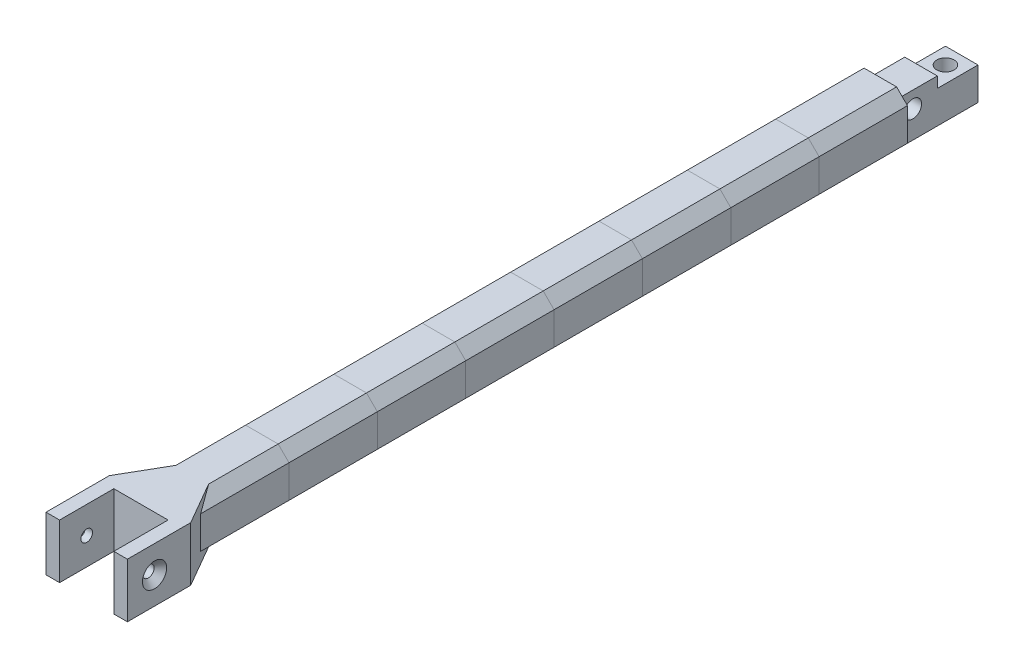
SolidWorks part; units mm, degrees
ref_plane "Front Plane" through (0, 0, 0) normal (0, 0, 1) x (1, 0, 0)
ref_plane "Top Plane" through (0, 0, 0) normal (0, 1, 0) x (1, 0, 0)
ref_plane "Right Plane" through (0, 0, 0) normal (1, 0, 0) x (0, 0, -1)
sketch "Sketch1" plane through (0, 0, 0) normal (0, 0, 1) x (1, 0, 0)
  line L1 (-10, -10) -> (10, -10)
  line L2 (-10, -10) -> (-10, 10)
  line L3 (-10, 10) -> (10, 10)
  line L4 (10, -10) -> (10, 10)
  line L5 (-10, -10) -> (10, 10) construction
  line L6 (-10, 10) -> (10, -10) construction
  point P0 (0, 0)
  dimension "D1" = 20
extrude "Boss-Extrude1" add sketch "Sketch1" along normal blind 302.5
sketch "Sketch2" plane through (0, 10, 0) normal (0, 1, 0) x (1, 0, 0)
  line L0 (0, -302.5) -> (0, -322.5) construction
  line L1 (10, -302.5) -> (-10, -302.5) construction
  line L2 (10, -302.5) -> (10, -322.5)
  line L3 (10, -322.5) -> (15, -322.5)
  line L4 (15, -322.5) -> (15, -299.1603)
  line L5 (15, -299.1603) -> (10, -290.5)
  line L6 (10, -302.5) -> (10, 0) construction
  line L7 (10, -290.5) -> (10, -302.5)
  line L8 (-10, -290.5) -> (-10, -302.5)
  line L9 (-15, -299.1603) -> (-10, -290.5)
  line L10 (-15, -322.5) -> (-15, -299.1603)
  line L11 (-10, -322.5) -> (-15, -322.5)
  line L12 (-10, -302.5) -> (-10, -322.5)
  point P10 (0, 0)
  dimension "D1" = 20
  dimension "D2" = 5
  dimension "D3" = 30
  dimension "D4" = 12
extrude "Boss-Extrude2" add sketch "Sketch2" against normal up to surface (20 mm away) up to face at (0, -10, 151.25)
sketch "Sketch3" plane through (15, 0, 0) normal (1, 0, 0) x (0, 0, -1)
  line L0 (-312.5, 10) -> (-312.5, -10) construction
  line L1 (-322.5, 10) -> (-299.1603, 10) construction
  line L2 (-299.1603, -10) -> (-322.5, -10) construction
  line L3 (-322.5, -10) -> (-322.5, 10) construction
  circle A0 centre (-312.5, 0) radius 2.15
  dimension "D2" = 4.3
  dimension "D1" = 10
extrude "Cut-Extrude1" cut sketch "Sketch3" against normal through all
sketch "Sketch4" plane through (0, 10, 0) normal (0, 1, 0) x (1, 0, 0)
  line L1 (-10, 0) -> (-6, 0)
  line L2 (-10, 0) -> (-10, -30)
  line L3 (-10, -30) -> (-6, -30)
  line L4 (-6, 0) -> (-6, -30)
  line L5 (10, 0) -> (6, 0)
  line L6 (10, 0) -> (10, -30)
  line L7 (10, -30) -> (6, -30)
  line L8 (6, 0) -> (6, -30)
  dimension "D1" = 30
  dimension "D2" = 12
extrude "Cut-Extrude2" cut sketch "Sketch4" against normal through all
chamfer "Chamfer1" distance 2.3 angle 45 2 edges at (-15, 0, 310.35) (15, 0, 310.35)
sketch "Sketch5" plane through (6, 0, 0) normal (1, 0, 0) x (0, 0, -1)
  line L1 (0, 10) -> (-15, 10)
  line L2 (0, 10) -> (0, 2)
  line L3 (0, 2) -> (-15, 2)
  line L4 (-15, 10) -> (-15, 2)
  line L5 (0, -10) -> (-30, -10) construction
  dimension "D1" = 12
  dimension "D2" = 15
extrude "Cut-Extrude3" cut sketch "Sketch5" against normal through all
sketch "Sketch6" plane through (0, 2, 0) normal (0, 1, 0) x (1, 0, 0)
  line L0 (-6, 0) -> (6, 0) construction
  circle A0 centre (0, -6) radius 3.2
  dimension "D1" = 6.4
  dimension "D2" = 6
extrude "Cut-Extrude4" cut sketch "Sketch6" against normal through all
sketch "Sketch7" plane through (6, 0, 0) normal (1, 0, 0) x (0, 0, -1)
  line L1 (-30, -10) -> (-30, 10) construction
  line L2 (-15, 10) -> (-30, 10) construction
  circle A0 centre (-24, 0) radius 3.2
  dimension "D1" = 6.4
  dimension "D2" = 6
  dimension "D3" = 10
extrude "Cut-Extrude5" cut sketch "Sketch7" against normal through all
sketch "Sketch10" plane through (0, 10, 0) normal (0, 1, 0) x (1, 0, 0)
  line L0 (10, -290.5) -> (10, -30) construction
  line L1 (-10, -30) -> (10, -30)
  line L2 (-10, -30) -> (-10, -62.5625)
  line L3 (-10, -62.5625) -> (10, -62.5625)
  line L4 (10, -30) -> (10, -62.5625)
  line L5 (-10, -290.5) -> (-10, -30) construction
  line L6 (10, -95.125) -> (-10, -95.125)
  line L7 (10, -95.125) -> (10, -127.6875)
  line L8 (10, -127.6875) -> (-10, -127.6875)
  line L9 (-10, -95.125) -> (-10, -127.6875)
  line L10 (10, -62.5625) -> (10, -95.125) construction
  line L11 (-10, -160.25) -> (10, -160.25)
  line L12 (-10, -160.25) -> (-10, -192.8125)
  line L13 (-10, -192.8125) -> (10, -192.8125)
  line L14 (10, -160.25) -> (10, -192.8125)
  line L15 (10, -225.375) -> (-10, -225.375)
  line L16 (10, -225.375) -> (10, -257.9375)
  line L17 (10, -257.9375) -> (-10, -257.9375)
  line L18 (-10, -225.375) -> (-10, -257.9375)
  line L19 (10, -127.6875) -> (10, -160.25) construction
  line L20 (10, -192.8125) -> (10, -225.375) construction
  line L21 (10, -257.9375) -> (10, -290.5) construction
extrude "Cut-Extrude7" cut sketch "Sketch10" against normal through all
sketch "Sketch11" plane through (0, 10, 0) normal (0, 1, 0) x (1, 0, 0)
  line L0 (-6, -30) -> (6, -30) construction
  line L1 (-10, -62.5625) -> (10, -62.5625)
  line L2 (-10, -62.5625) -> (-10, -30)
  line L3 (-10, -30) -> (10, -30)
  line L4 (10, -62.5625) -> (10, -30)
  line L5 (10, -95.125) -> (-10, -95.125)
  line L6 (10, -95.125) -> (10, -127.6875)
  line L7 (10, -127.6875) -> (-10, -127.6875)
  line L8 (-10, -95.125) -> (-10, -127.6875)
  line L9 (-10, -160.25) -> (10, -160.25)
  line L10 (-10, -160.25) -> (-10, -192.8125)
  line L11 (-10, -192.8125) -> (10, -192.8125)
  line L12 (10, -160.25) -> (10, -192.8125)
  line L13 (-10, -225.375) -> (10, -225.375)
  line L14 (-10, -225.375) -> (-10, -257.9375)
  line L15 (-10, -257.9375) -> (10, -257.9375)
  line L16 (10, -225.375) -> (10, -257.9375)
  line L17 (10, -95.125) -> (10, -62.5625) construction
extrude "Boss-Extrude3" add sketch "Sketch11" against normal up to surface (20 mm away) separate body up to face at (0, -10, 78.8437)
chamfer "Chamfer3" distance 4 angle 45 4 edges at (10, 10, 274.2187) (-10, 10, 274.2187) (-10, -10, 274.2187) (10, -10, 274.2187)
sketch "Sketch12" plane through (0, 0, 30) normal (0, 0, -1) x (-1, 0, 0)
  line L17 (-10, 10) -> (-6, 10)
  line L18 (-10, 10) -> (10, 10) construction
  line L19 (-6, 10) -> (-10, 6)
  line L20 (-10, -10) -> (-10, 10) construction
  line L21 (-10, 6) -> (-10, 10)
  line L22 (-10, -10) -> (-10, -6)
  line L23 (-10, -6) -> (-6, -10)
  line L24 (10, -10) -> (-10, -10) construction
  line L25 (-6, -10) -> (-10, -10)
  line L35 (6, 10) -> (10, 10)
  line L36 (6, 10) -> (15, 10) construction
  line L37 (10, 10) -> (10, 6)
  line L38 (10, 6) -> (6, 10)
  line L39 (10, -10) -> (10, -6)
  line L40 (10, -10) -> (10, 10) construction
  line L41 (10, -6) -> (6, -10)
  line L42 (6, -10) -> (10, -10)
  line L43 (10, -6) -> (10, 6) construction
  dimension "D1" = 4
extrude "Cut-Extrude8" cut sketch "Sketch12" against normal up to surface (227.9375 mm away) up to face at (0, 0, 257.9375)
sketch "Sketch13" plane through (6, 0, 0) normal (1, 0, 0) x (0, 0, -1)
  line L1 (-15, 10) -> (-30, 10)
  line L2 (-15, 10) -> (-15, 6)
  line L3 (-15, 6) -> (-30, 6)
  line L4 (-30, 10) -> (-30, 6)
extrude "Cut-Extrude9" cut sketch "Sketch13" against normal through all
